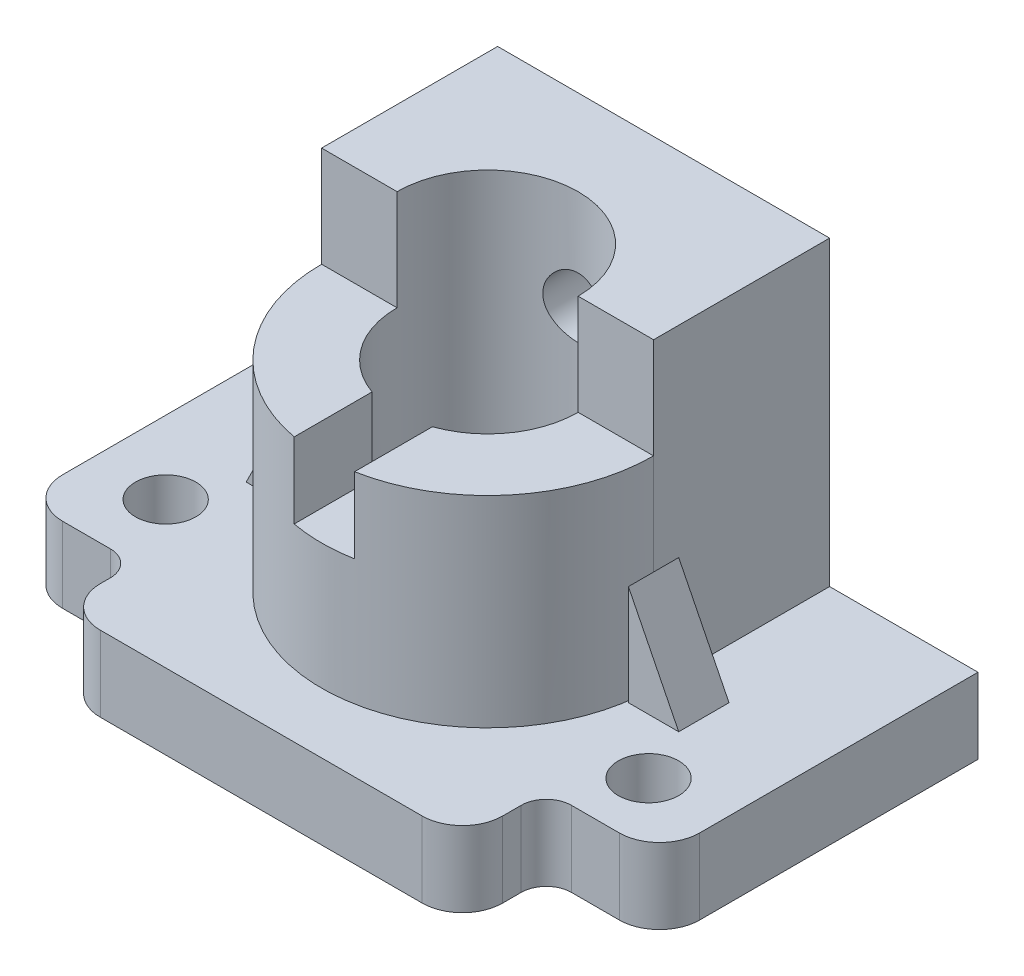
SolidWorks part; units mm, degrees
ref_plane "前视基准面" through (0, 0, 0) normal (0, 0, 1) x (1, 0, 0)
ref_plane "上视基准面" through (0, 0, 0) normal (0, 1, 0) x (1, 0, 0)
ref_plane "右视基准面" through (0, 0, 0) normal (1, 0, 0) x (0, 0, -1)
other "Configuration Table"
sketch "草图1" plane through (0, 0, 0) normal (0, 1, 0) x (1, 0, 0)
  line L0 (0, 0) -> (0, -65)
  line L1 (0, -65) -> (22.5, -65)
  line L2 (22.5, -65) -> (22.5, -80)
  line L3 (22.5, -80) -> (102.5, -80)
  line L4 (102.5, -80) -> (102.5, -63.3233)
  line L5 (102.5, -63.3233) -> (125, -63.3233)
  line L6 (125, -63.3233) -> (125, 0)
  line L7 (125, 0) -> (0, 0)
  line L8 (62.5, -80) -> (62.5, 32.2184) construction
  circle A0 centre (14.5, -51) radius 6
  circle A1 centre (110.5, -51) radius 6
  point P3 (102.5, -71.6616)
  dimension "D6" = 12
  dimension "D1" = 80
  dimension "D2" = 125
  dimension "D3" = 65
  dimension "D4" = 80
  dimension "D5" = 51
  dimension "D7" = 96
extrude "凸台-拉伸1" add sketch "草图1" along normal blind 15
fillet "圆角1" radius 8 2 edges at (125, 7.5, 63.3233) (0, 7.5, 65)
fillet "圆角2" radius 8 2 edges at (102.5, 7.5, 80) (22.5, 7.5, 80)
fillet "圆角3" radius 5 2 edges at (22.5, 7.5, 65) (102.5, 7.5, 63.3233)
sketch "草图2" plane through (0, 15, 0) normal (0, 1, 0) x (1, 0, 0)
  line L1 (62.5, 0) -> (62.5, -30.5322) construction
  line L2 (125, 0) -> (0, 0) construction
  line L3 (62.5, -35) -> (29.5, -35)
  line L4 (29.5, -35) -> (29.5, 0)
  line L5 (29.5, 0) -> (95.5, 0)
  line L6 (95.5, 0) -> (95.5, -35)
  line L7 (95.5, -35) -> (80.5, -35)
  line L8 (29.5, -35) -> (44.5, -35)
  circle A0 centre (62.5, -35) radius 18
  arc A1 (29.5, -35) -> (95.5, -35) centre (62.5, -35) ccw
  line M10 (125, 0) -> (0, 0)
  dimension "D1" = 66
  dimension "D2" = 36
  dimension "D3" = 35
extrude "凸台-拉伸3" add sketch "草图2" along normal blind 60 contours L1 A0 L7 L6 M10 | L1 L5 L4 L3 A0 | L1 A0 L3 A1 | A0 L1 A1 L7
sketch "草图5" plane through (0, 75, 0) normal (0, 1, 0) x (1, 0, 0)
  line L0 (29.5, -35) -> (95.5, -35)
  line L3 (29.5, 0) -> (29.5, -35)
  line L4 (95.5, -35) -> (95.5, 0)
  line L5 (95.5, 0) -> (29.5, 0)
  line L6 (29.5, 0) -> (29.5, -35)
  line L7 (95.5, -35) -> (95.5, 0)
  line L8 (95.5, 0) -> (29.5, 0)
  arc A1 (29.5, -35) -> (95.5, -35) centre (62.5, -35) ccw
  arc A2 (29.5, -35) -> (95.5, -35) centre (62.5, -35) ccw
  arc M6 (29.5, -35) -> (95.5, -35) centre (62.5, -35) ccw
  circle M9 centre (62.5, -35) radius 18
  dimension "D1" = 0
extrude "切除-拉伸1" cut sketch "草图5" against normal blind 20 contours L0 M6 M9
sketch "草图6" plane through (0, 55, 0) normal (0, 1, 0) x (1, 0, 0)
  line L0 (29.5, 0) -> (29.5, -35) construction
  line L1 (29.5, -35) -> (44.5, -35) construction
  line L2 (80.5, -35) -> (95.5, -35) construction
  line L3 (95.5, -35) -> (95.5, 0) construction
  line L4 (95.5, 0) -> (29.5, 0) construction
  line L5 (44.5, -35) -> (29.5, -35) construction
  line L6 (95.5, -35) -> (80.5, -35) construction
  line L7 (29.5, 0) -> (29.5, -35)
  line L8 (29.5, -35) -> (44.5, -35)
  line L9 (80.5, -35) -> (95.5, -35)
  line L10 (95.5, -35) -> (95.5, 0)
  line L11 (95.5, 0) -> (29.5, 0)
  line L12 (44.5, -35) -> (29.5, -35)
  line L13 (95.5, -35) -> (80.5, -35)
  line L14 (62.5, -35) -> (62.5, -68)
  line L15 (62.5, -48.3011) -> (56.5, -48.3011)
  line L16 (56.5, -48.3011) -> (56.5, -67.45)
  line L17 (62.5, -48.3011) -> (68.5, -48.3011)
  line L18 (68.5, -48.3011) -> (68.5, -67.45)
  arc A0 (80.5, -35) -> (44.5, -35) centre (62.5, -35) ccw construction
  arc A1 (29.5, -35) -> (95.5, -35) centre (62.5, -35) ccw construction
  arc A2 (44.5, -35) -> (80.5, -35) centre (62.5, -35) ccw construction
  arc A3 (80.5, -35) -> (44.5, -35) centre (62.5, -35) ccw
  arc A4 (29.5, -35) -> (95.5, -35) centre (62.5, -35) ccw
  arc A5 (44.5, -35) -> (80.5, -35) centre (62.5, -35) ccw
  circle A6 centre (62.5, -35) radius 33
  arc M8 (29.5, -35) -> (95.5, -35) centre (62.5, -35) ccw
  arc M10 (80.5, -35) -> (44.5, -35) centre (62.5, -35) cw
  dimension "D1" = 6
  dimension "D2" = 6
extrude "切除-拉伸2" cut sketch "草图6" against normal blind 15 contours L16 L14 M10 M8 | L18 L14 M10 M8
sketch "草图7" plane through (0, 0, 0) normal (0, 0, -1) x (-1, 0, 0)
  line L0 (-62.5, 75) -> (-62.5, 10.869) construction
  line L1 (-95.5, 75) -> (-29.5, 75) construction
  circle A0 centre (-62.5, 55) radius 6
  dimension "D2" = 12
  dimension "D1" = 20
extrude "切除-拉伸3" cut sketch "草图7" against normal up to next
ref_plane "基准面1" through (0, 0, 30) normal (0, 0, -1) x (-1, 0, 0)
sketch "草图10" plane through (0, 0, 30) normal (0, 0, -1) x (-1, 0, 0)
  line L0 (-95.5, 15) -> (-105.5, 15)
  line L1 (-125, 15) -> (-95.5, 15) construction
  line L2 (-105.5, 15) -> (-95.5, 35)
  line L3 (-95.5, 75) -> (-95.5, 15) construction
  line L4 (-95.5, 35) -> (-95.5, 15)
  line L5 (-62.5, 75) -> (-62.5, 56.0093) construction
  line L6 (-95.5, 75) -> (-29.5, 75) construction
  line L7 (-19.5, 15) -> (-29.5, 35)
  line L8 (-29.5, 15) -> (-19.5, 15)
  line L9 (-29.5, 35) -> (-29.5, 15)
  dimension "D1" = 20
  dimension "D2" = 10
extrude "凸台-拉伸4" add sketch "草图10" against normal blind 10
